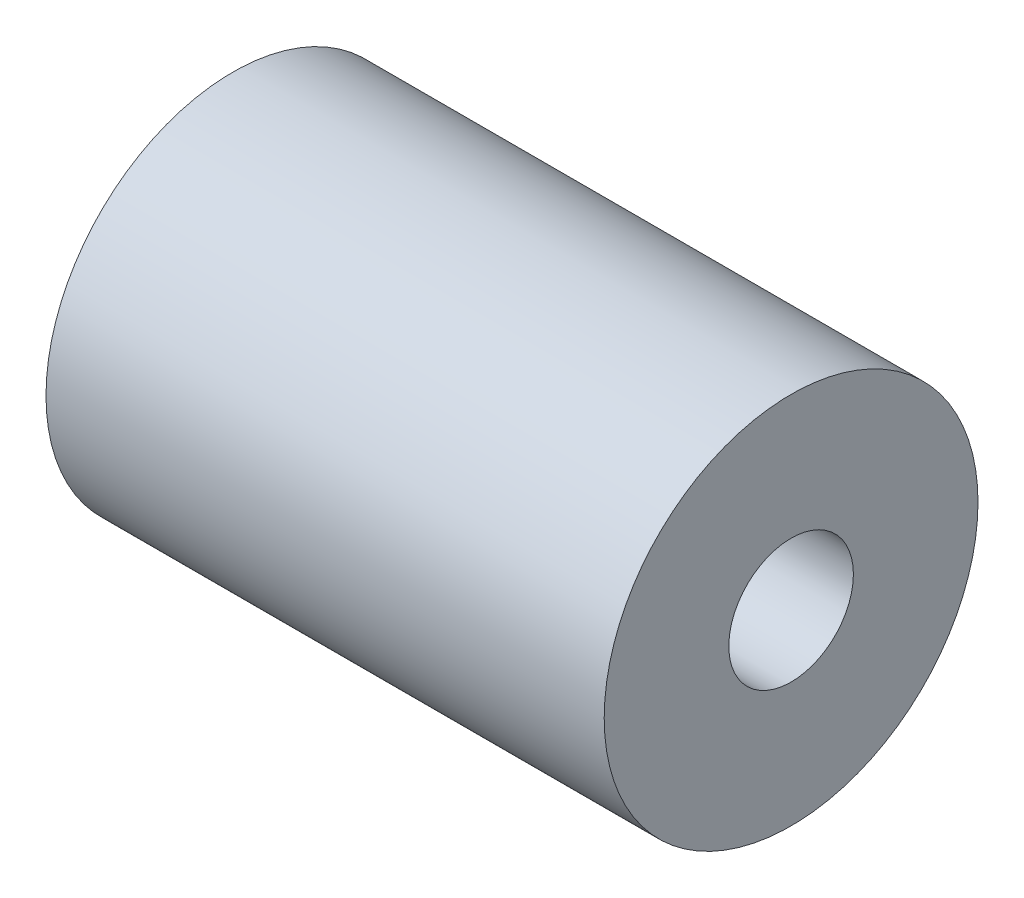
SolidWorks part; units mm, degrees
material "Silicon Rubber"
ref_plane "Front Plane" through (0, 0, 0) normal (0, 0, 1) x (1, 0, 0)
ref_plane "Top Plane" through (0, 0, 0) normal (0, 1, 0) x (1, 0, 0)
ref_plane "Right Plane" through (0, 0, 0) normal (1, 0, 0) x (0, 0, -1)
sketch "Sketch1" plane through (0, 0, 0) normal (1, 0, 0) x (0, 0, -1)
  circle A0 centre (0, 0) radius 3.175
  circle A1 centre (0, 0) radius 9.525
  dimension "D1" = 6.35
  dimension "D2" = 19.05
extrude "Boss-Extrude1" add sketch "Sketch1" along normal blind 28.448
